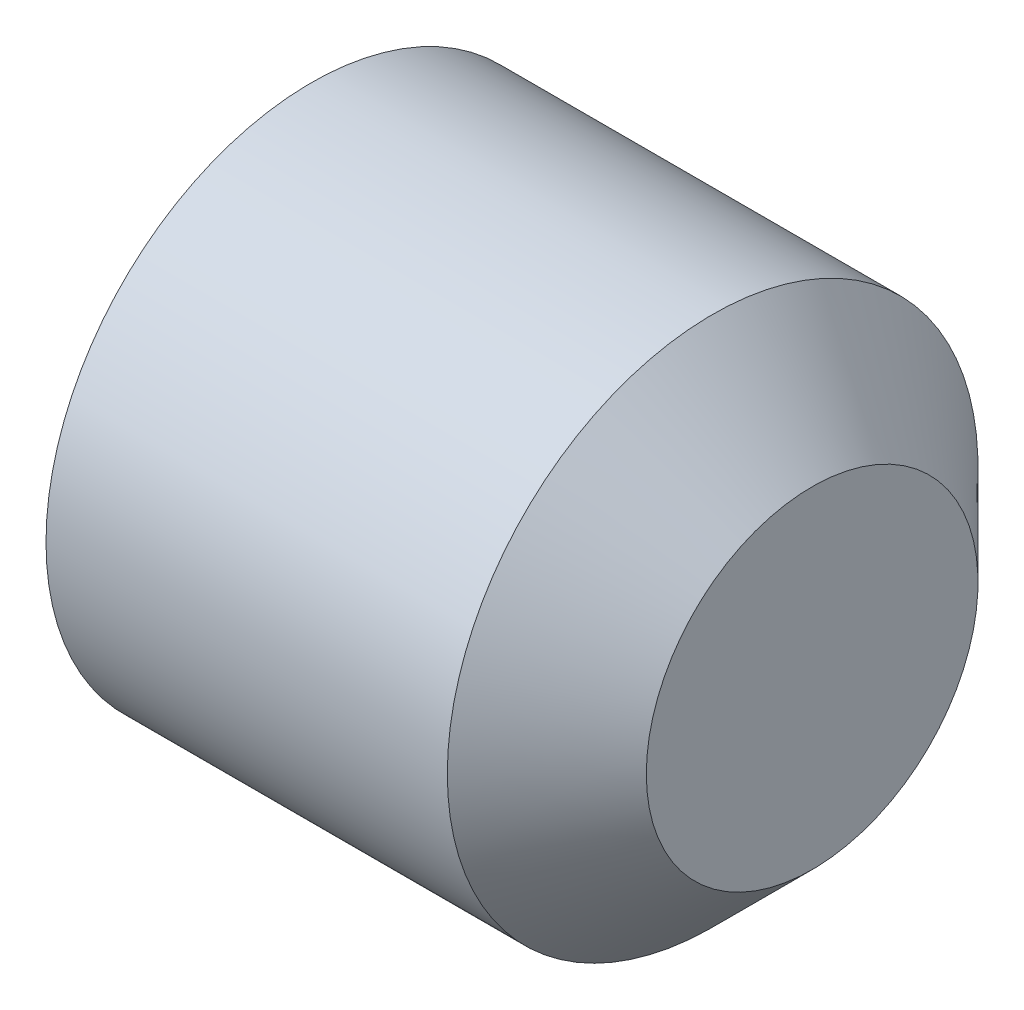
SolidWorks part; units mm, degrees
ref_plane "Plane1" through (0, 0, 0) normal (0, 0, 1) x (1, 0, 0)
ref_plane "Plane2" through (0, 0, 0) normal (0, 1, 0) x (1, 0, 0)
ref_plane "Plane3" through (0, 0, 0) normal (1, 0, 0) x (0, 0, -1)
sketch "BodySke" plane through (0, 0, 0) normal (0, 0, 1) x (1, 0, 0)
  line L0 (0, 0) -> (0, 1.61)
  line L1 (0, 1.61) -> (0.2252, 2)
  line L2 (0.2252, 2) -> (3.25, 2)
  line L3 (3.25, 2) -> (4, 1.25)
  line L4 (4, 0) -> (0, 0)
  line L5 (-12.7, 0) -> (88.9, 0) construction
  line L6 (4, 1.25) -> (4, 0)
  line L7 (4, 1.25) -> (4, 10.775) construction
  line L8 (0, -1.61) -> (0.2252, -2) construction
  line L9 (0.7, 15.875) -> (0.7, -3.175) construction
  line L10 (3.25, -2) -> (4, -1.25) construction
  dimension "Length" = 4
  dimension "Diameter" = 4
  dimension "Drive_ch_ang" = 60
  dimension "Minor_dia" = 3.22
  dimension "Cup_nose_ang" = 45
  dimension "Cup_dia" = 2.5
  dimension "Advance" = 0.7
revolve "BaseBody" add sketch "BodySke" angle 360 about L5
cosmetic thread "ThreadCosmetic" parameters "Thread_minor"=3.22
sketch "Sketch2" plane through (0, 0, 0) normal (-1, 0, 0) x (0, 0, 1)
  line L0 (0.5774, 1) -> (-0.5774, 1)
  line L1 (-0.5774, 1) -> (-1.1547, 0)
  line L2 (0.5774, 1) -> (1.1547, 0)
  line L3 (0.5774, -1) -> (1.1547, 0)
  line L4 (0.5774, -1) -> (-0.5774, -1)
  line L5 (-0.5774, -1) -> (-1.1547, 0)
  dimension "Hex_size" = 2
  dimension "D2" = 1
  dimension "D3" = 1
extrude "Hex" cut sketch "Sketch2" against normal blind 1.8
sketch "Sketch4" plane through (0, 4.7709, -0.5249) normal (-1, 0, 0) x (0, 0, 1)
  line L0 (0.5249, -4.7709) -> (1.7694, -4.7709)
  line L1 (0.5249, -4.7709) -> (6.6732, -1.2211) construction
  line L2 (0.5249, -4.7709) -> (1.1471, -3.6931)
  line L3 (1.5335, -4.5113) -> (1.7149, -4.4066)
  line L4 (1.254, -4.0272) -> (1.4354, -3.9225)
  arc A0 (1.5335, -4.5113) -> (1.254, -4.0272) centre (0.5249, -4.7709) ccw
  arc A1 (1.7694, -4.7709) -> (1.7149, -4.4066) centre (0.5249, -4.7709) ccw
  arc A2 (1.1471, -3.6931) -> (1.4354, -3.9225) centre (0.5249, -4.7709) cw
  circle A3 centre (0.5249, -4.7709) radius 1.0415 construction
  circle A4 centre (0.5249, -4.7709) radius 1.2445 construction
  dimension "D1" = 30
  dimension "Spline_n_dim" = 2.083
  dimension "Spline_m_dim" = 2.489
  dimension "Spline_a_dim" = 60
  dimension "D3" = 0.2795
  dimension "Spline_p_dim" = 0.559
extrude "Spline6" [suppressed] cut sketch "Sketch4" against normal blind 1.8
pattern_circular "CirPattern1" [suppressed] count 6 every 60 about axis through (-12.7, 0, 0) along (1, 0, 0)
sketch "Sketch5" plane through (0, 0.6556, 6.6316) normal (-1, 0, 0) x (0, 0, 1)
  line L0 (-6.6316, -0.6556) -> (-5.3871, -0.6556)
  line L1 (-6.6316, -0.6556) -> (-1.6115, 4.3645) construction
  line L2 (-6.6316, -0.6556) -> (-6.6316, 0.5889)
  line L3 (-5.6975, -0.1168) -> (-5.5765, 0.0043)
  line L4 (-6.0928, 0.2785) -> (-5.9717, 0.3996)
  line L5 (-6.0928, 0.2785) -> (-5.6975, -0.1168)
  arc A1 (-5.3871, -0.6556) -> (-5.5765, 0.0043) centre (-6.6316, -0.6556) ccw
  arc A2 (-6.6316, 0.5889) -> (-5.9717, 0.3996) centre (-6.6316, -0.6556) cw
  circle A3 centre (-6.6316, -0.6556) radius 1.0415 construction
  circle A4 centre (-6.6316, -0.6556) radius 1.2445 construction
  dimension "D1" = 45
  dimension "Spline_n_dim" = 2.083
  dimension "Spline_m_dim" = 2.489
  dimension "Spline_a_dim" = 90
  dimension "D3" = 0.2795
  dimension "Spline_p_dim" = 0.559
extrude "Spline4" [suppressed] cut sketch "Sketch5" against normal blind 1.8
pattern_circular "CirPattern2" [suppressed] count 4 every 90 about axis through (-12.7, 0, 0) along (1, 0, 0)
sketch "ThdSchSke" plane through (0, 0, 0) normal (0, 0, 1) x (1, 0, 0)
  line L0 (0.2252, -1.61) -> (-0.0479, -2)
  line L1 (0.2252, -1.61) -> (0.4982, -2)
  line L2 (0.4982, -2) -> (0.4982, -2.5)
  line L3 (-3.175, 0) -> (5.1513, 0) construction
  line L4 (0.2252, 2) -> (0.2252, -2) construction
  line L5 (0.4982, -2.5) -> (-0.0479, -2.5)
  line L6 (-0.0479, -2.5) -> (-0.0479, -2)
  dimension "Thread_minor" = 3.22
  dimension "Diameter" = 4
  dimension "SideAngle" = 55
  dimension "VeeAngle" = 70
  dimension "Overcut" = 5
revolve "ThreadSchematic" [suppressed] cut sketch "ThdSchSke" angle 360 about L3
pattern_linear "ThdSchPat" [suppressed]
equation "\"D2@Sketch2\" = \"Hex_size@Sketch2\" / 2"
equation "\"D3@Sketch2\" = \"Hex_size@Sketch2\" / 2"
equation "\"Thread_minor@ThreadCosmetic\" = \"Minor_dia@BodySke\""
equation "\"D1@Sketch4\" = \"Spline_a_dim@Sketch4\" / 2"
equation "\"D3@Sketch4\" = \"Spline_p_dim@Sketch4\" / 2"
equation "\"D2@CirPattern1\" = \"Spline_a_dim@Sketch4\""
equation "\"Num_teeth@CirPattern1\" = 360 / \"D2@CirPattern1\""
equation "\"Spline_a_dim@Sketch5\" = 90"
equation "\"Spline_p_dim@Sketch5\" = \"Spline_p_dim@Sketch4\""
equation "\"Spline_m_dim@Sketch5\" = \"Spline_m_dim@Sketch4\""
equation "\"Spline_n_dim@Sketch5\" = \"Spline_n_dim@Sketch4\""
equation "\"D1@Sketch5\" = \"Spline_a_dim@Sketch5\" / 2"
equation "\"D3@Sketch5\" = \"Spline_p_dim@Sketch5\" / 2"
equation "\"Key_eng@Spline4\" = \"Key_eng@Spline6\""
equation "\"Thread_minor@ThdSchSke\" = \"Thread_minor@ThreadCosmetic\""
equation "\"Diameter@ThdSchSke\" = \"Diameter@BodySke\""
equation "\"Overcut@ThdSchSke\" = \"Diameter@BodySke\" * 1.25"
equation "\"Num_threads@ThdSchPat\" = int( (\"Length@BodySke\" - ( ( ( \"Diameter@BodySke\" - \"Minor_dia@BodySke\" ) * 0.5 ) / tan( \"Drive_ch_ang@BodySke\" * 0.017453292 ) ) - ( ( ( \"Diameter@BodySke\" - \"Cup_dia@BodySke\" ) * 0.5 ) * tan( \"Cup_nose_ang@BodySke\" * 0.017453292 ) ) ) / \"Advance@BodySke\" + 0.999 )  + 1"
equation "\"Advance@ThdSchPat\" = (\"Length@BodySke\" - ( ( ( \"Diameter@BodySke\" - \"Minor_dia@BodySke\" ) * 0.5 ) / tan( \"Drive_ch_ang@BodySke\" * 0.017453292 ) ) - ( ( ( \"Diameter@BodySke\" - \"Cup_dia@BodySke\" ) * 0.5 ) * tan( \"Cup_nose_ang@BodySke\" * 0.017453292 ) ) ) /  (\"Num_threads@ThdSchPat\" - 1) 'relax it"
equation "' \"Num_threads@ThdSchPat\" = \"Num_threads@ThdSchPat\" - sgn( \"Num_threads@ThdSchPat\" - 1) '---chamfered tips only---"
